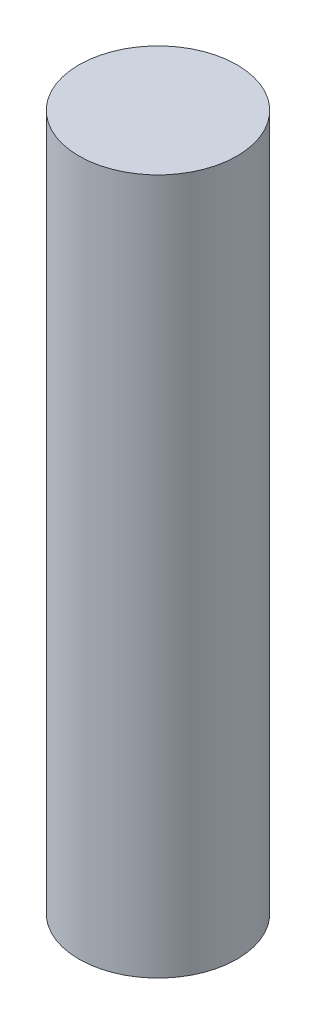
SolidWorks part; units mm, degrees
ref_plane "Front Plane" through (0, 0, 0) normal (0, 0, 1) x (1, 0, 0)
ref_plane "Top Plane" through (0, 0, 0) normal (0, 1, 0) x (1, 0, 0)
ref_plane "Right Plane" through (0, 0, 0) normal (1, 0, 0) x (0, 0, -1)
sketch "Sketch1" plane through (0, 0, 0) normal (0, 1, 0) x (1, 0, 0)
  circle A0 centre (0, 0) radius 5
extrude "Boss-Extrude1" add sketch "Sketch1" along normal blind 44
